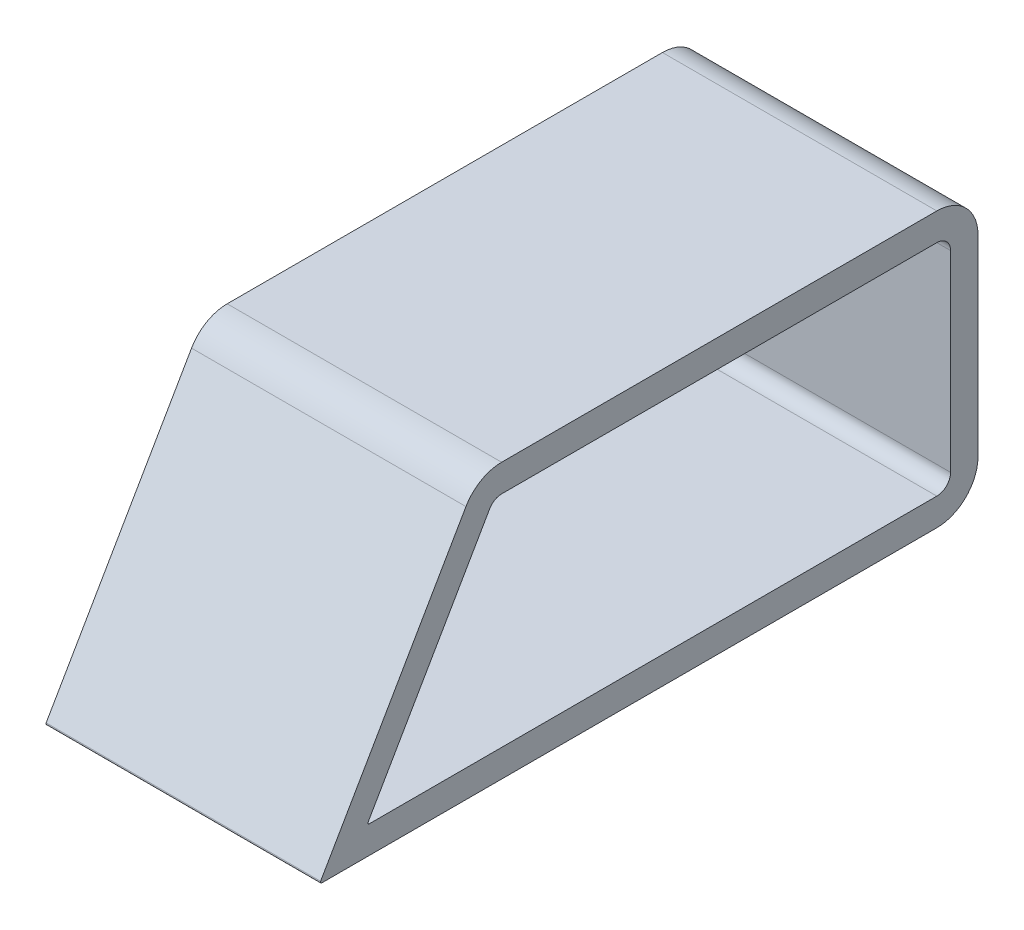
SolidWorks part; units mm, degrees
ref_plane "Front Plane" through (0, 0, 0) normal (0, 0, 1) x (1, 0, 0)
ref_plane "Top Plane" through (0, 0, 0) normal (0, 1, 0) x (1, 0, 0)
ref_plane "Right Plane" through (0, 0, 0) normal (1, 0, 0) x (0, 0, -1)
sketch "Sketch1" plane through (0, 0, 0) normal (1, 0, 0) x (0, 0, -1)
  line L0 (0, 0) -> (271.2969, 469.9)
  line L1 (337.288, 508) -> (1143, 508)
  line L2 (1219.2, 431.8) -> (1219.2, 76.2)
  line L3 (1143, 0) -> (0, 0)
  line L4 (337.288, 457.2) -> (1143, 457.2)
  line L5 (1168.4, 431.8) -> (1168.4, 76.2)
  line L6 (1143, 50.8) -> (87.9882, 50.8)
  line L7 (87.9882, 50.8) -> (315.291, 444.5)
  arc A0 (271.2969, 469.9) -> (337.288, 508) centre (337.288, 431.8) cw
  arc A1 (1219.2, 76.2) -> (1143, 0) centre (1143, 76.2) cw
  arc A2 (1143, 508) -> (1219.2, 431.8) centre (1143, 431.8) cw
  arc A3 (1143, 457.2) -> (1168.4, 431.8) centre (1143, 431.8) cw
  arc A4 (1168.4, 76.2) -> (1143, 50.8) centre (1143, 76.2) cw
  arc A5 (315.291, 444.5) -> (337.288, 457.2) centre (337.288, 431.8) cw
  point P9 (1219.2, 0)
  dimension "D4" = 76.2
  dimension "D1" = 508
  dimension "D2" = 1219.2
  dimension "D3" = 60
  dimension "D5" = 50.8
extrude "Boss-Extrude1" add sketch "Sketch1" along normal mid plane 508
fillet "Fillet1" radius 2.54 2 edges at (0, 50.8, -87.9882) (0, 0, 0)
